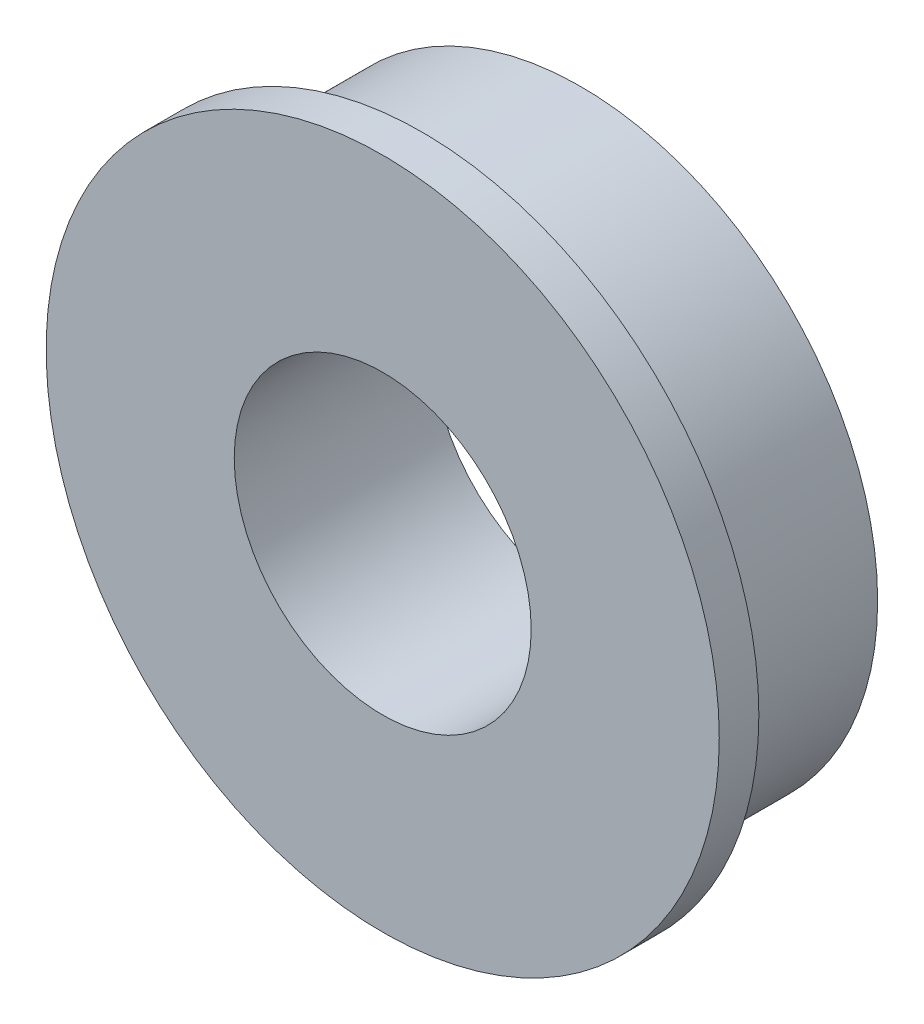
SolidWorks part; units mm, degrees
ref_plane "前视基准面" through (0, 0, 0) normal (0, 0, 1) x (1, 0, 0)
ref_plane "上视基准面" through (0, 0, 0) normal (0, 1, 0) x (1, 0, 0)
ref_plane "右视基准面" through (0, 0, 0) normal (1, 0, 0) x (0, 0, -1)
sketch "草图1" plane through (0, 0, 0) normal (0, 0, 1) x (1, 0, 0)
  circle A0 centre (0, 0) radius 3
  circle A1 centre (0, 0) radius 6
  dimension "D1" = 6
  dimension "D2" = 12
extrude "凸台-拉伸1" add sketch "草图1" along normal blind 4
sketch "草图2" plane through (0, 0, 4) normal (0, 0, 1) x (1, 0, 0)
  circle A0 centre (0, 0) radius 3
  circle A1 centre (0, 0) radius 6.8
  dimension "D1" = 13.6
extrude "凸台-拉伸2" add sketch "草图2" against normal blind 0.8
